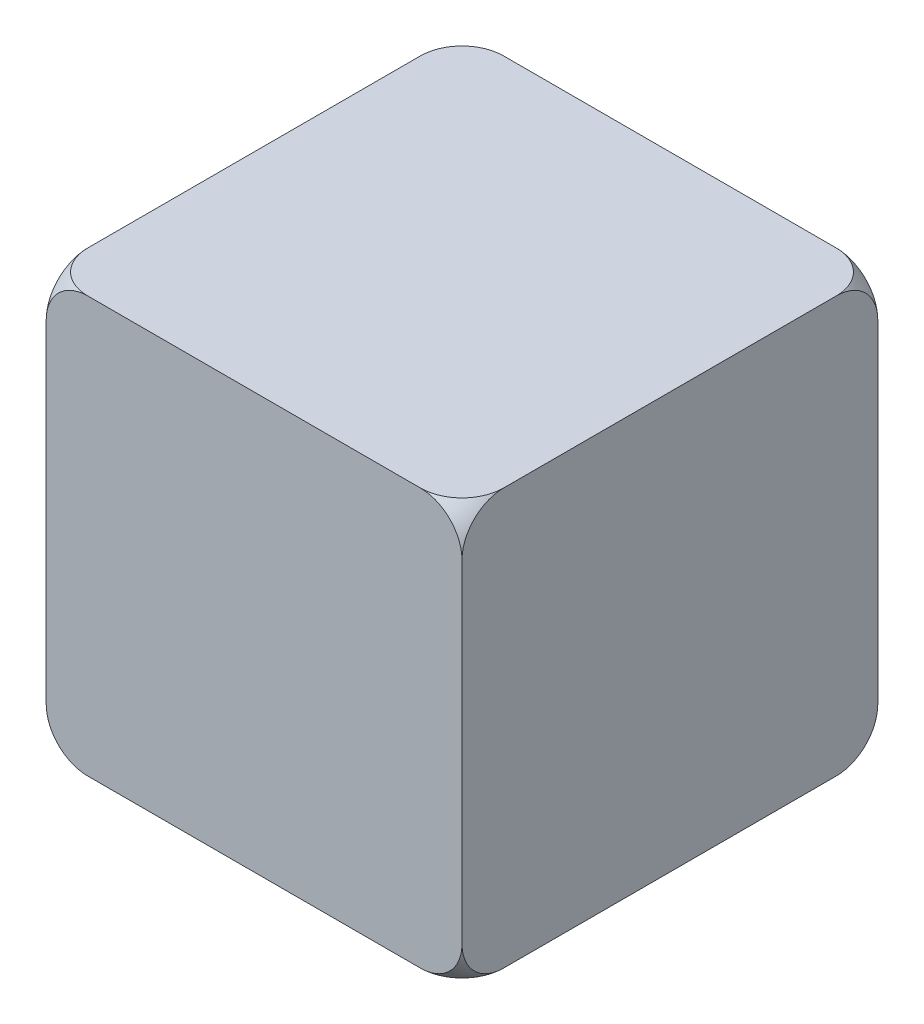
SolidWorks part; units mm, degrees
ref_plane "Plano frontal" through (0, 0, 0) normal (0, 0, 1) x (1, 0, 0)
ref_plane "Plano superior" through (0, 0, 0) normal (0, 1, 0) x (1, 0, 0)
ref_plane "Plano direito" through (0, 0, 0) normal (1, 0, 0) x (0, 0, -1)
sketch3d "3DSketch1"
  line L0 (0, 0, 0) -> (1, 0, 0) construction
  line L1 (1, 0, 0) -> (9, 0, 0) construction
  line L2 (9, 0, 0) -> (10, 0, 0) construction
  line L3 (0, 0, 0) -> (0, 0, 1) construction
  line L4 (0, 0, 1) -> (0, 0, 9) construction
  line L5 (0, 0, 9) -> (0, 0, 10) construction
  line L6 (10, 0, 0) -> (10, 0, 1) construction
  line L7 (0, 0, 10) -> (1, 0, 10) construction
  line L8 (10, 0, 1) -> (10, 0, 9) construction
  line L9 (1, 0, 10) -> (9, 0, 10) construction
  line L10 (10, 0, 9) -> (10, 0, 10) construction
  line L11 (9, 0, 10) -> (10, 0, 10) construction
  line L12 (0, 0, 9) -> (1, 0, 9) construction
  line L13 (1, 0, 10) -> (1, 0, 9) construction
  line L14 (10, 0, 9) -> (9, 0, 9) construction
  line L15 (9, 0, 10) -> (9, 0, 9) construction
  line L16 (1, 0, 9) -> (1, 1, 9) construction
  line L17 (9, 0, 9) -> (9, 1, 9) construction
  line L18 (1, 1, 9) -> (1, 9, 9) construction
  line L19 (9, 1, 9) -> (9, 9, 9) construction
  line L20 (1, 9, 9) -> (1, 10, 9) construction
  line L21 (9, 9, 9) -> (9, 10, 9) construction
  line L22 (0, 0, 1) -> (1, 0, 1) construction
  line L23 (1, 0, 1) -> (1, 1, 1) construction
  line L24 (1, 0, 0) -> (1, 0, 1) construction
  line L25 (1, 1, 1) -> (1, 9, 1) construction
  line L26 (10, 0, 1) -> (9, 0, 1) construction
  line L27 (1, 9, 1) -> (1, 10, 1) construction
  line L28 (9, 0, 0) -> (9, 0, 1) construction
  line L29 (9, 0, 1) -> (9, 1, 1) construction
  line L30 (9, 1, 1) -> (9, 9, 1) construction
  line L31 (9, 9, 1) -> (9, 10, 1) construction
  line L32 (1, 0, 1) -> (2, 0, 1) construction
  line L33 (9, 0, 1) -> (8, 0, 1) construction
  line L34 (1, 1, 1) -> (-0.4142, 1, 1)
  line L35 (1, 1, 1) -> (2.4142, 1, 1)
  line L36 (9, 1, 1) -> (7.5858, 1, 1)
  line L37 (9, 1, 1) -> (10.4142, 1, 1)
  arc A0 (-0.4142, 1, 1) -> (2.4142, 1, 1) centre (1, 1, 1) ccw
  arc A1 (7.5858, 1, 1) -> (10.4142, 1, 1) centre (9, 1, 1) ccw
  point P32 (1, 1, 2.4142)
  point P34 (9, 1, 2.4142)
  dimension "D1" = 1
  dimension "D2" = 1
  dimension "D3" = 10
  dimension "D4" = 1
  dimension "D5" = 1
  dimension "D6" = 10
  dimension "D7" = 1
  dimension "D8" = 1
  dimension "D9" = 1
  dimension "D10" = 1
  dimension "D11" = 1
  dimension "D12" = 1
  dimension "D13" = 1
  dimension "D14" = 1
  dimension "D15" = 10
  dimension "D16" = 10
  dimension "D17" = 1
  dimension "D18" = 1
  dimension "D19" = 10
  dimension "D20" = 1
  dimension "D21" = 1
  dimension "D22" = 10
  dimension "D23" = 1
  dimension "D24" = 1
ref_plane "Plano1" through (0, 0, 1) normal (0, 0, 1) x (1, 0, 0)
sketch "Esboço2" plane through (0, 0, 1) normal (0, 0, 1) x (1, 0, 0)
  line L0 (1, 1) -> (-0.4142, 1) construction
  line L1 (1, 1) -> (2.4142, 1) construction
  line L2 (1, 1) -> (-0.4142, 1)
  line L3 (1, 1) -> (2.4142, 1)
  line L4 (9, 1) -> (7.5858, 1) construction
  line L5 (9, 1) -> (10.4142, 1) construction
  line L6 (9, 1) -> (7.5858, 1)
  line L7 (9, 1) -> (10.4142, 1)
  arc A0 (-0.4142, 1) -> (2.4142, 1) centre (1, 1) ccw construction
  arc A1 (-0.4142, 1) -> (2.4142, 1) centre (1, 1) ccw
  arc A2 (7.5858, 1) -> (10.4142, 1) centre (9, 1) ccw construction
  arc A3 (7.5858, 1) -> (10.4142, 1) centre (9, 1) ccw
revolve "Revolução1" add sketch "Esboço2" angle 360 about L2
pattern_linear "Padrão linear2" count 2 spacing 8 along (0, 0, 1) count 2 spacing 8 along (0, 1, 0) of bodies 101 102
sketch "Esboço3" plane through (0, 0, 0) normal (0, 0, 1) x (1, 0, 0)
  line L0 (1, 9) -> (1, 10)
  line L1 (0, 0) -> (1, 0)
  line L2 (0, 0) -> (0, 1)
  line L3 (0, 10) -> (1, 10)
  line L4 (10, 0) -> (10, 1)
  line L5 (-5, -5) -> (15, -5)
  line L6 (-5, -5) -> (-5, 15)
  line L7 (-5, 15) -> (15, 15)
  line L8 (15, -5) -> (15, 15)
  line L9 (1, 9) -> (0, 9)
  line L10 (1, 1) -> (1, 0)
  line L11 (1, 1) -> (0, 1)
  line L12 (9, 1) -> (9, 0)
  line L13 (9, 1) -> (10, 1)
  line L14 (9, 9) -> (10, 9)
  line L15 (9, 9) -> (9, 10)
  line L16 (10, 9) -> (10, 10)
  line L17 (0, 9) -> (0, 10)
  line L18 (9, 0) -> (10, 0)
  line L19 (9, 10) -> (10, 10)
  circle A0 centre (9, 9) radius 1.4142 construction
  circle A1 centre (1, 9) radius 1.4142 construction
  circle A2 centre (1, 1) radius 1.4142 construction
  circle A3 centre (9, 1) radius 1.4142 construction
  circle A4 centre (9, 9) radius 1.4142 construction
  circle A5 centre (1, 9) radius 1.4142 construction
  circle A6 centre (1, 1) radius 1.4142 construction
  circle A7 centre (9, 1) radius 1.4142 construction
  dimension "D1" = 10
  dimension "D2" = 5
  dimension "D3" = 5
  dimension "D4" = 5
  dimension "D5" = 5
  dimension "D6" = 10
extrude "Corte-extrusão1" cut sketch "Esboço3" against normal through all and the other way through all
sketch "Esboço4" plane through (0, 0, 0) normal (1, 0, 0) x (0, 0, -1)
  line L0 (-9, 9) -> (-10, 9)
  line L1 (0, 0) -> (-1, 0)
  line L2 (0, 0) -> (0, 1)
  line L3 (0, 10) -> (-1, 10)
  line L4 (-10, 0) -> (-10, 1)
  line L5 (-15, 15) -> (5, 15)
  line L6 (-15, 15) -> (-15, -5)
  line L7 (-15, -5) -> (5, -5)
  line L8 (5, 15) -> (5, -5)
  line L9 (-8, 9) -> (-10, 9) construction
  line L10 (-9, 9) -> (-9, 10)
  line L11 (-9, 1) -> (-9, 0)
  line L12 (-8, 1) -> (-10, 1) construction
  line L13 (-9, 1) -> (-10, 1)
  line L14 (-1, 1) -> (-1, 0)
  line L15 (0, 1) -> (-2, 1) construction
  line L16 (-1, 1) -> (0, 1)
  line L17 (-1, 9) -> (0, 9)
  line L18 (0, 9) -> (-2, 9) construction
  line L19 (-1, 9) -> (-1, 10)
  line L20 (-10, 9) -> (-10, 10)
  line L21 (0, 9) -> (0, 10)
  line L22 (-9, 0) -> (-10, 0)
  line L23 (-9, 10) -> (-10, 10)
  dimension "D2" = 5
  dimension "D3" = 5
  dimension "D4" = 5
  dimension "D5" = 5
extrude "Corte-extrusão3" cut sketch "Esboço4" against normal blind 10 and the other way blind 20
sketch "Esboço5" plane through (0, 0, 1) normal (0, 0, 1) x (1, 0, 0)
  line L1 (10, 10) -> (0, 10)
  line L2 (10, 10) -> (10, 0)
  line L3 (10, 0) -> (0, 0)
  line L4 (0, 10) -> (0, 0)
extrude "Ressalto-extrusão1" add sketch "Esboço5" along normal up to vertex (8 mm away) up to point (9, 9, 9)
sketch "Esboço6" plane through (1, 0, 0) normal (1, 0, 0) x (0, 0, -1)
  line L1 (-10, 10) -> (0, 10)
  line L2 (-10, 10) -> (-10, 0)
  line L3 (-10, 0) -> (0, 0)
  line L4 (0, 10) -> (0, 0)
extrude "Ressalto-extrusão2" add sketch "Esboço6" along normal up to vertex (8 mm away) up to point (9, 9, 9)
sketch "Esboço7" plane through (0, 1, 0) normal (0, 1, 0) x (1, 0, 0)
  line L1 (10, -10) -> (0, -10)
  line L2 (10, -10) -> (10, 0)
  line L3 (10, 0) -> (0, 0)
  line L4 (0, -10) -> (0, 0)
extrude "Ressalto-extrusão3" add sketch "Esboço7" along normal up to vertex (8 mm away) up to point (9, 9, 9)
